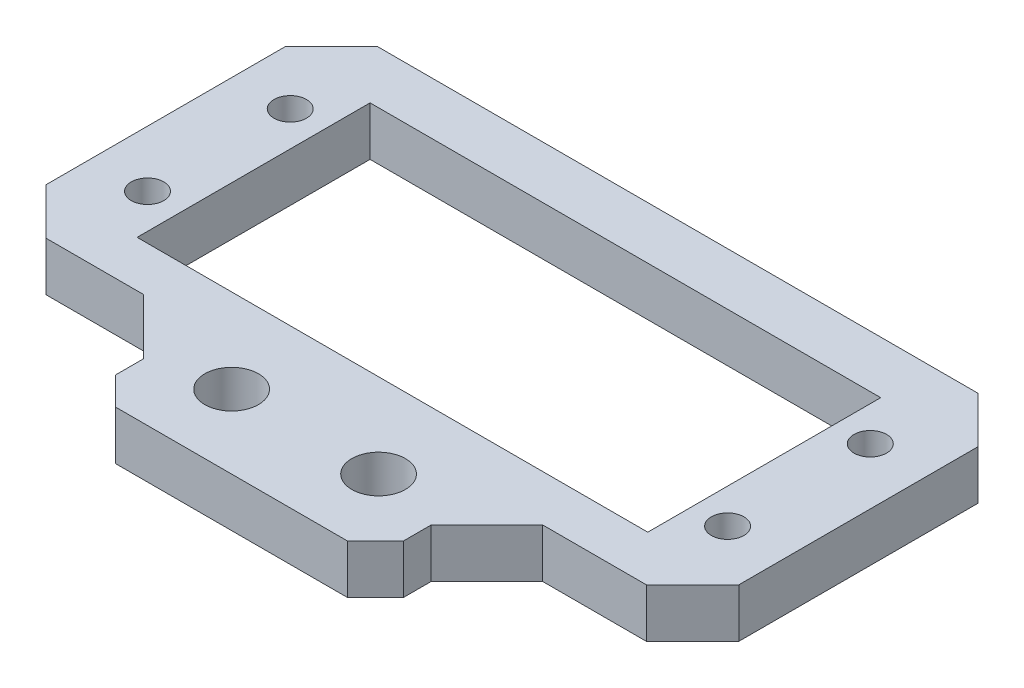
SolidWorks part; units mm, degrees
ref_plane "Front Plane" through (0, 0, 0) normal (0, 0, 1) x (1, 0, 0)
ref_plane "Top Plane" through (0, 0, 0) normal (0, 1, 0) x (1, 0, 0)
ref_plane "Right Plane" through (0, 0, 0) normal (1, 0, 0) x (0, 0, -1)
sketch "Sketch1" plane through (0, 0, 0) normal (0, 1, 0) x (1, 0, 0)
  line L0 (-12.025, 0) -> (54.175, 0) construction
  line L1 (59.9865, 21.9) -> (-17.8365, 21.9)
  line L2 (65.9865, -15.1) -> (65.9865, 15.9)
  line L3 (59.9865, -21.1) -> (46.5514, -21.1)
  line L4 (-17.8365, 21.9) -> (-23.8365, 15.9)
  line L5 (-23.8365, -15.1) -> (-23.8365, 15.9)
  line L6 (-23.8365, -15.1) -> (-17.8365, -21.1)
  line L7 (54.175, -15.1) -> (-12.025, -15.1)
  line L8 (54.175, -15.1) -> (54.175, 15.1)
  line L9 (54.175, 15.1) -> (-12.025, 15.1)
  line L10 (-12.025, -15.1) -> (-12.025, 15.1)
  line L11 (54.175, -15.1) -> (-12.025, 15.1) construction
  line L12 (54.175, 15.1) -> (-12.025, -15.1) construction
  line L13 (21.075, 15.1) -> (21.075, -15.1) construction
  line L14 (35.7118, -35.5527) -> (5.6382, -35.5527)
  line L15 (2.025, -31.9395) -> (2.025, -28.3264)
  line L16 (2.025, -28.3264) -> (-5.2014, -21.1)
  line L17 (65.9865, -15.1) -> (59.9865, -21.1)
  line L18 (59.9865, 21.9) -> (65.9865, 15.9)
  line L19 (20.675, -18.7956) -> (20.675, -33.2484) construction
  line L20 (-5.2014, -21.1) -> (-17.8365, -21.1)
  line L21 (39.325, -28.3264) -> (46.5514, -21.1)
  line L22 (39.325, -31.9395) -> (39.325, -28.3264)
  line L23 (2.025, -31.9395) -> (5.6382, -35.5527)
  line L24 (39.325, -31.9395) -> (35.7118, -35.5527)
  circle A0 centre (58.675, 9.25) radius 2.1082
  circle A1 centre (58.675, -9.25) radius 2.1082
  circle A2 centre (-16.525, -9.25) radius 2.1082
  circle A3 centre (-16.525, 9.25) radius 2.1082
  circle A4 centre (11.15, -26.022) radius 3.475
  circle A5 centre (30.2, -26.022) radius 3.475
  point P0 (0, 0)
  point P4 (21.075, 21.9)
  point P6 (21.075, 0)
  point P25 (21.075, -21.1)
  dimension "D5" = 4.2164
  dimension "D1" = 9.525
  dimension "D2" = 10.922
  dimension "D3" = 66.2
  dimension "D4" = 30.2
  dimension "D6" = 9.25
  dimension "D7" = 4.5
extrude "Boss-Extrude1" add sketch "Sketch1" along normal blind 6.35
